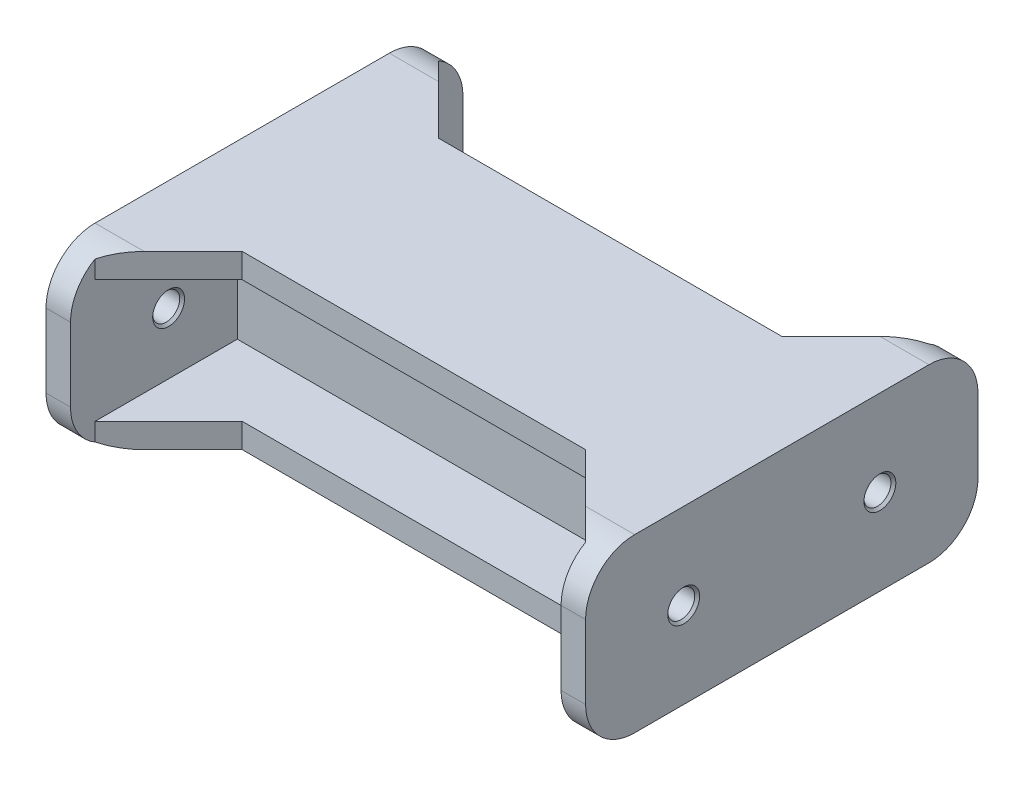
SolidWorks part; units mm, degrees
ref_plane "前视基准面" through (0, 0, 0) normal (0, 0, 1) x (1, 0, 0)
ref_plane "上视基准面" through (0, 0, 0) normal (0, 1, 0) x (1, 0, 0)
ref_plane "右视基准面" through (0, 0, 0) normal (1, 0, 0) x (0, 0, -1)
sketch "草图1" plane through (0, 0, 0) normal (1, 0, 0) x (0, 0, -1)
  line L1 (-40, 5) -> (40, 5)
  line L2 (-40, 5) -> (-40, -15)
  line L3 (-40, -15) -> (40, -15)
  line L4 (40, 5) -> (40, -15)
  dimension "D1" = 80
  dimension "D2" = 40
  dimension "D3" = 20
  dimension "D4" = 5
extrude "凸台-拉伸1" add sketch "草图1" along normal blind 5
sketch "草图3" plane through (5, 0, 0) normal (1, 0, 0) x (0, 0, -1)
  line L6 (-6, 5) -> (6, 5)
  line L7 (40, 5) -> (-40, 5) construction
  line L8 (6, 5) -> (6, -10)
  line L9 (6, -10) -> (20, -10)
  line L10 (20, -10) -> (20, -15)
  line L11 (-40, -15) -> (40, -15) construction
  line L12 (20, -15) -> (-20, -15)
  line L13 (-20, -15) -> (-20, -10)
  line L14 (-20, -10) -> (-6, -10)
  line L15 (-6, -10) -> (-6, 5)
  dimension "D1" = 6
  dimension "D2" = 6
  dimension "D3" = 5
  dimension "D4" = 5
  dimension "D5" = 20
  dimension "D6" = 20
extrude "凸台-拉伸3" add sketch "草图3" along normal blind 100
sketch "草图5" plane through (0, 0, 0) normal (-1, 0, 0) x (0, 0, 1)
  line L0 (-6, -10) -> (-6, 5) construction
  line L1 (6, 5) -> (-6, 5)
  line L2 (6, 5) -> (6, 20)
  line L3 (6, 20) -> (-6, 20)
  line L4 (-6, 5) -> (-6, 20)
  dimension "D1" = 15
extrude "凸台-拉伸4" add sketch "草图5" against normal blind 105
sketch "草图6" plane through (0, 0, 0) normal (-1, 0, 0) x (0, 0, 1)
  line L1 (6, 20) -> (40, 20)
  line L2 (6, 20) -> (6, 5)
  line L3 (6, 5) -> (40, 5)
  line L4 (40, 20) -> (40, 5)
  line L5 (-6, 20) -> (-40, 20)
  line L6 (-6, 20) -> (-6, 5)
  line L7 (-6, 5) -> (-40, 5)
  line L8 (-40, 20) -> (-40, 5)
extrude "凸台-拉伸5" add sketch "草图6" against normal blind 5
sketch "草图7" plane through (105, 0, 0) normal (1, 0, 0) x (0, 0, -1)
  line L1 (-40, -15) -> (40, -15)
  line L2 (-40, -15) -> (-40, 20)
  line L3 (-40, 20) -> (40, 20)
  line L4 (40, -15) -> (40, 20)
extrude "凸台-拉伸6" add sketch "草图7" along normal blind 5
sketch "草图8" plane through (0, -15, 0) normal (0, -1, 0) x (1, 0, 0)
  line L0 (90, 20) -> (105, 35)
  line L1 (105, 20) -> (5, 20) construction
  line L2 (105, 40) -> (105, 20) construction
  line L3 (105, 35) -> (105, 20)
  line L4 (105, 20) -> (90, 20)
  line L5 (0, 0) -> (50000, 0) construction
  line L6 (55, 20) -> (55, 50020) construction
  line L7 (105, -20) -> (90, -20)
  line L8 (105, -35) -> (105, -20)
  line L9 (90, -20) -> (105, -35)
  line L10 (5, 20) -> (20, 20)
  line L11 (5, 35) -> (5, 20)
  line L12 (20, 20) -> (5, 35)
  line L13 (20, -20) -> (5, -35)
  line L14 (5, -35) -> (5, -20)
  line L15 (5, -20) -> (20, -20)
  point P13 (55, 20)
  dimension "D1" = 15
  dimension "D2" = 15
extrude "凸台-拉伸7" add sketch "草图8" against normal blind 5
sketch "草图9" plane through (110, 0, 0) normal (1, 0, 0) x (0, 0, -1)
  line L0 (0, 0) -> (0, -50000) construction
  line L1 (40, 20) -> (-40, 20) construction
  circle A0 centre (20, 2.5) radius 2.75
  circle A1 centre (-20, 2.5) radius 2.75
  dimension "D1" = 5.5
  dimension "D2" = 17.5
  dimension "D3" = 20
extrude "切除-拉伸1" cut sketch "草图9" against normal through all
chamfer "倒角1" distance 0.5 angle 45 8 edges at (5, 2.5, 17.25) (0, 2.5, 22.75) (105, 2.5, 22.75) (110, 2.5, 22.75) (5, 2.5, -22.75) (0, 2.5, -22.75) (105, 2.5, -17.25) (110, 2.5, -22.75)
fillet "圆角1" radius 10 4 edges at (107.5, -15, -40) (107.5, -15, 40) (2.5, -15, 40) (2.5, -15, -40)
sketch "草图10" plane through (0, 20, 0) normal (0, 1, 0) x (1, 0, 0)
  line L6 (5, 35) -> (5, 6)
  line L7 (5, 6) -> (105, 6)
  line L8 (105, 6) -> (105, 35)
  line L9 (105, 35) -> (90, 20)
  line L10 (90, 20) -> (20, 20)
  line L11 (20, 20) -> (5, 35)
  line L12 (5, 35) -> (5, 6)
  line L13 (5, 6) -> (105, 6)
  line L14 (105, 6) -> (105, 35)
  line L15 (105, 35) -> (90, 20)
  line L16 (90, 20) -> (20, 20)
  line L17 (20, 20) -> (5, 35)
  line L18 (5, -6) -> (5, -35)
  line L19 (5, -35) -> (20, -20)
  line L20 (20, -20) -> (90, -20)
  line L21 (90, -20) -> (105, -35)
  line L22 (105, -35) -> (105, -6)
  line L23 (105, -6) -> (5, -6)
  line L24 (5, -6) -> (5, -35)
  line L25 (5, -35) -> (20, -20)
  line L26 (20, -20) -> (90, -20)
  line L27 (90, -20) -> (105, -35)
  line L28 (105, -35) -> (105, -6)
  line L29 (105, -6) -> (5, -6)
  dimension "D1" = 0
  dimension "D2" = 0
extrude "凸台-拉伸8" add sketch "草图10" against normal blind 5
fillet "圆角2" radius 10 4 edges at (107.5, 20, 40) (107.5, 20, -40) (2.5, 20, 40) (2.5, 20, -40)
